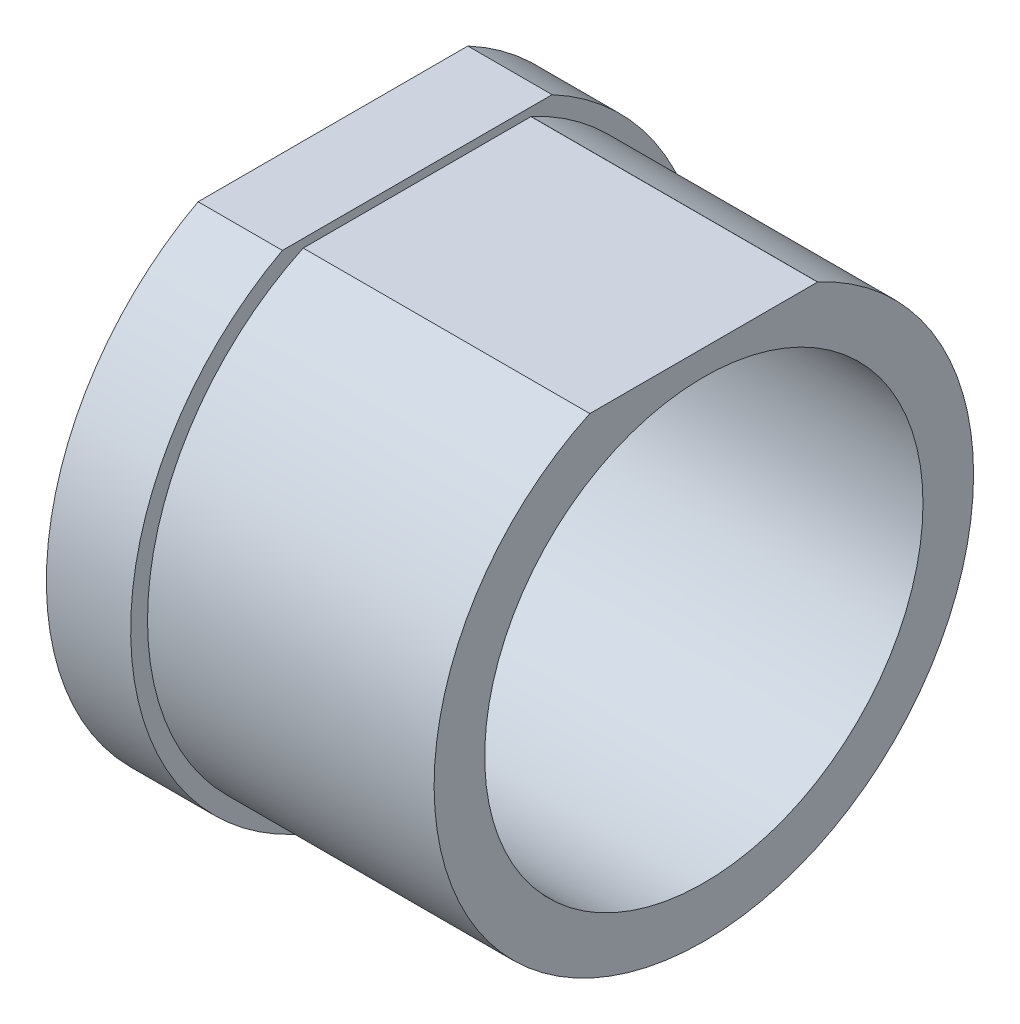
SolidWorks part; units mm, degrees
material "Copper"
ref_plane "Front Plane" through (0, 0, 0) normal (0, 0, 1) x (1, 0, 0)
ref_plane "Top Plane" through (0, 0, 0) normal (0, 1, 0) x (1, 0, 0)
ref_plane "Right Plane" through (0, 0, 0) normal (1, 0, 0) x (0, 0, -1)
sketch "Sketch1" plane through (0, 0, 0) normal (1, 0, 0) x (0, 0, -1)
  circle A0 centre (0, 0) radius 34
extrude "Boss-Extrude1" add sketch "Sketch1" along normal blind 10
sketch "Sketch2" plane through (10, 0, 0) normal (1, 0, 0) x (0, 0, -1)
  circle A0 centre (0, 0) radius 32
extrude "Boss-Extrude2" add sketch "Sketch2" along normal blind 34
sketch "Sketch3" plane through (44, 0, 0) normal (1, 0, 0) x (0, 0, -1)
  circle A0 centre (0, 0) radius 26
extrude "Cut-Extrude1" cut sketch "Sketch3" against normal through all
sketch "Sketch4" plane through (44, 0, 0) normal (1, 0, 0) x (0, 0, -1)
  line L1 (-13.5619, 36.688) -> (13.4918, 36.688)
  line L2 (-13.5619, 36.688) -> (-13.5619, 29)
  line L3 (-13.5619, 29) -> (13.4918, 29)
  line L4 (13.4918, 36.688) -> (13.4918, 29)
  circle A0 centre (0, 0) radius 32 construction
  circle A1 centre (0, 0) radius 26 construction
  dimension "D1" = 6
  dimension "D2" = 29
  dimension "D3" = 7.688
  dimension "D4" = 27.0537
  dimension "D5" = 13.5619
extrude "Cut-Extrude2" cut sketch "Sketch4" against normal blind 34
sketch "Sketch5" plane through (0, 0, 0) normal (-1, 0, 0) x (0, 0, 1)
  line L1 (-23.6606, 37.2904) -> (25.7815, 37.2904)
  line L2 (-23.6606, 37.2904) -> (-23.6606, 30)
  line L3 (-23.6606, 30) -> (25.7815, 30)
  line L4 (25.7815, 37.2904) -> (25.7815, 30)
  circle A0 centre (0, 0) radius 34 construction
  circle A1 centre (0, 0) radius 26 construction
  dimension "D1" = 8
  dimension "D2" = 30
  dimension "D3" = 7.2904
  dimension "D4" = 49.4421
  dimension "D5" = 23.6606
extrude "Cut-Extrude3" cut sketch "Sketch5" against normal up to next
equation "\"D2@Sketch4\"=26+\"D1@Sketch4\"/2"
equation "\"D2@Sketch5\"=26+\"D1@Sketch5\"/2"
